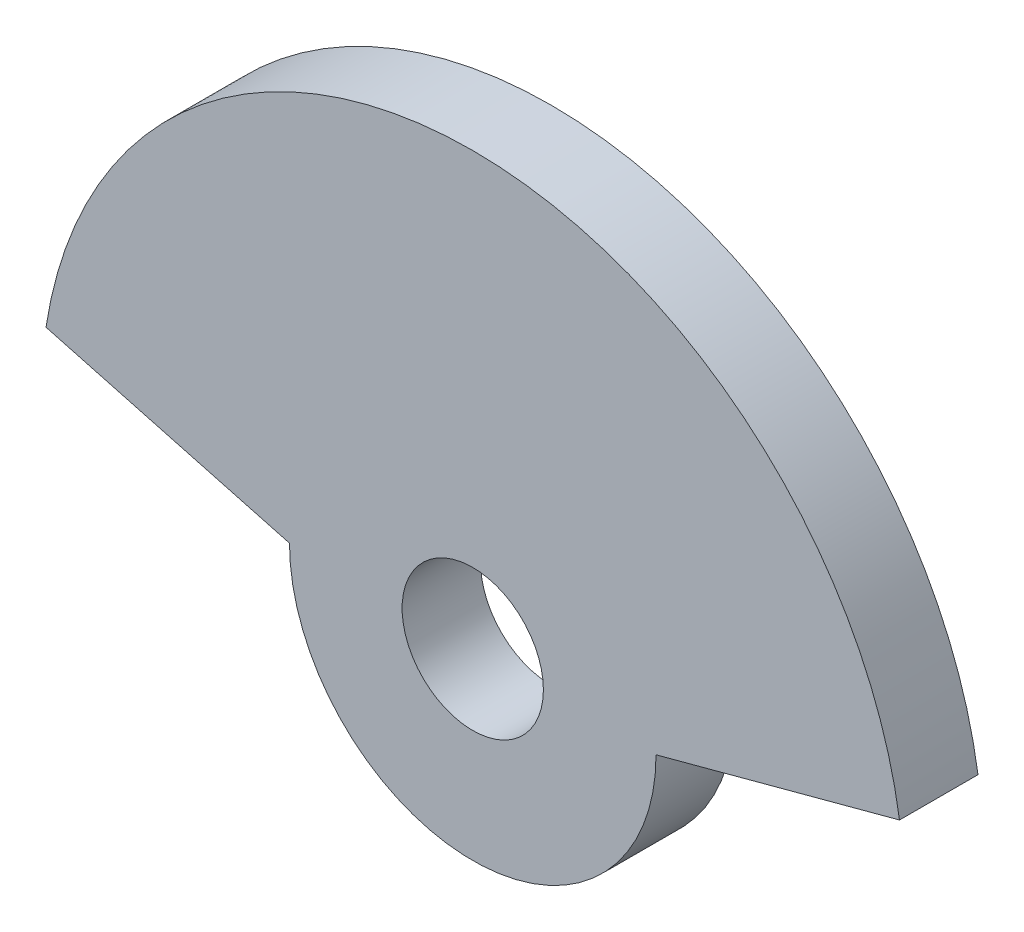
SolidWorks part; units mm, degrees
ref_plane "Płaszczyzna przednia" through (0, 0, 0) normal (0, 0, 1) x (1, 0, 0)
ref_plane "Płaszczyzna górna" through (0, 0, 0) normal (0, 1, 0) x (1, 0, 0)
ref_plane "Płaszczyzna prawa" through (0, 0, 0) normal (1, 0, 0) x (0, 0, -1)
sketch "Szkic1" plane through (0, 0, 0) normal (0, 0, 1) x (1, 0, 0)
  line L0 (-23.35, 0) -> (-54.3684, 8.3114)
  line L1 (23.35, 0) -> (54.3684, 8.3114)
  line L2 (0, 0) -> (0, 55) construction
  circle A0 centre (0, 0) radius 9
  arc A1 (-23.35, 0) -> (23.35, 0) centre (0, 0) ccw
  arc A2 (54.3684, 8.3114) -> (-54.3684, 8.3114) centre (0, 0) ccw
  dimension "D1" = 18
  dimension "D2" = 23.35
  dimension "D3" = 55
  dimension "D4" = 150
extrude "Dodanie-wyciągnięcie1" add sketch "Szkic1" along normal blind 10
